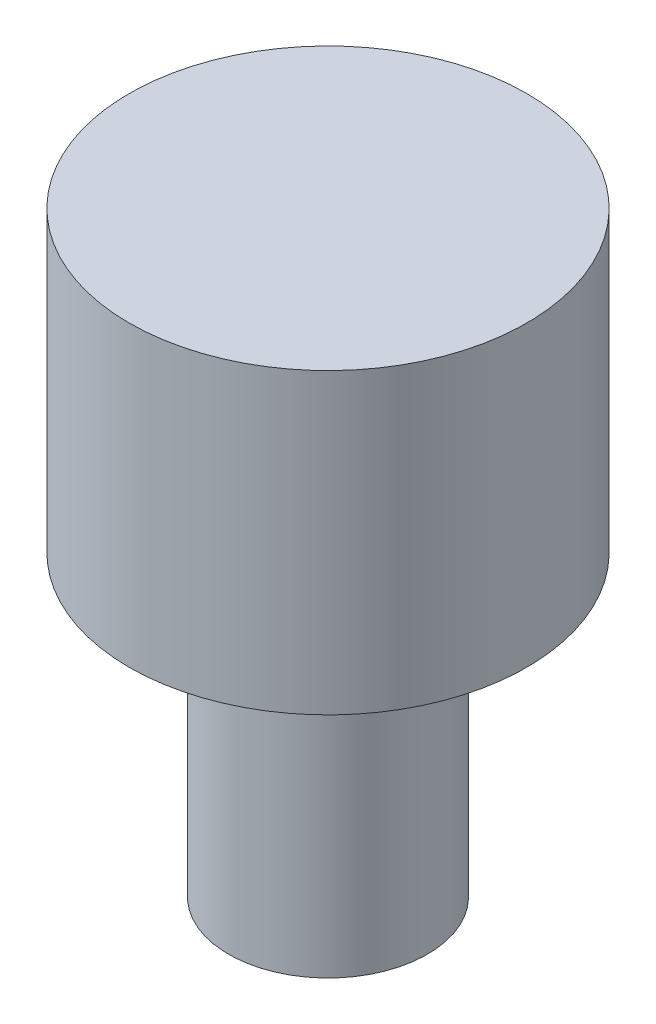
SolidWorks part; units mm, degrees
ref_plane "Ön Düzlem" through (0, 0, 0) normal (0, 0, 1) x (1, 0, 0)
ref_plane "Üst Düzlem" through (0, 0, 0) normal (0, 1, 0) x (1, 0, 0)
ref_plane "Sağ Düzlem" through (0, 0, 0) normal (1, 0, 0) x (0, 0, -1)
sketch "Çizim2" plane through (0, 0, 0) normal (0, 1, 0) x (1, 0, 0)
  circle A0 centre (0, 0) radius 20
  point P2 (0, 0)
  point P3 (0, 0)
  dimension "D1" = 40
extrude "Yükseklik-Ekstrüzyon1" add sketch "Çizim2" against normal blind 30
sketch "Çizim3" plane through (0, -30, 0) normal (0, -1, 0) x (1, 0, 0)
  circle A0 centre (0, 0) radius 10
  dimension "D1" = 20
extrude "Yükseklik-Ekstrüzyon2" add sketch "Çizim3" along normal blind 30
